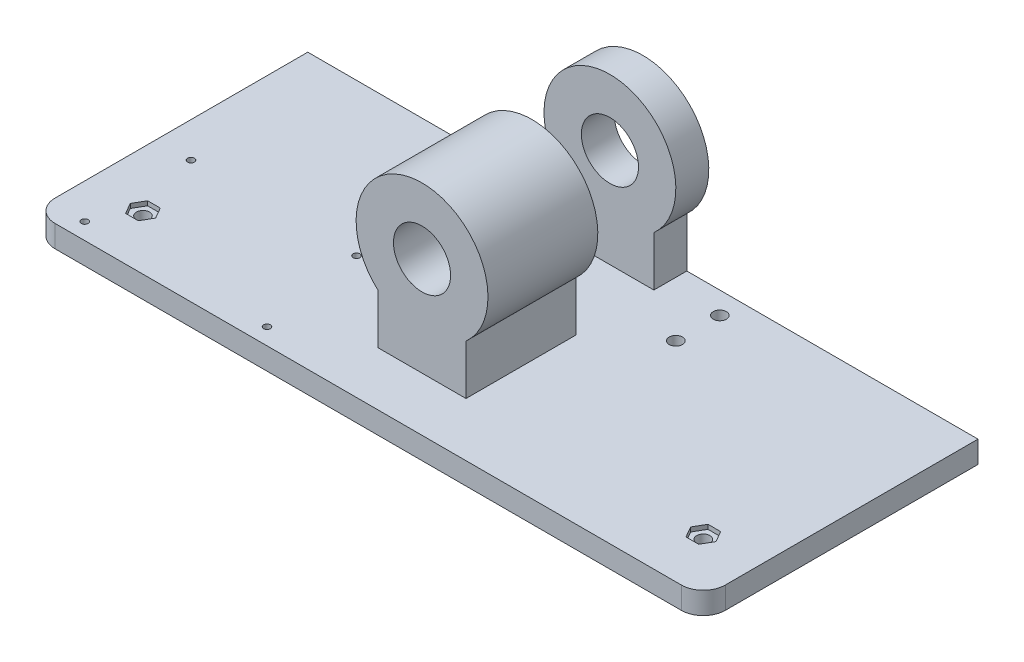
SolidWorks part; units mm, degrees
ref_plane "Front Plane" through (0, 0, 0) normal (0, 0, 1) x (1, 0, 0)
ref_plane "Top Plane" through (0, 0, 0) normal (0, 1, 0) x (1, 0, 0)
ref_plane "Right Plane" through (0, 0, 0) normal (1, 0, 0) x (0, 0, -1)
sketch "Sketch1" plane through (0, 0, 0) normal (0, 1, 0) x (1, 0, 0)
  line L0 (152.5, 125) -> (152.5, 0) construction
  line L1 (0, 0) -> (305, 0)
  line L2 (0, 0) -> (0, 125)
  line L3 (0, 125) -> (305, 125)
  line L4 (305, 0) -> (305, 125)
  line L5 (25, 100) -> (280, 100) construction
  line L6 (280, 25) -> (280, 100) construction
  line L7 (25, 25) -> (280, 25) construction
  line L8 (25, 25) -> (25, 100) construction
  line L9 (152.5, 62.5) -> (25, 62.5) construction
  line L10 (30.7735, 100) -> (27.8868, 105) construction
  line L11 (27.8868, 105) -> (22.1132, 105) construction
  line L12 (22.1132, 105) -> (19.2265, 100) construction
  line L13 (19.2265, 100) -> (22.1132, 95) construction
  line L14 (22.1132, 95) -> (27.8868, 95) construction
  line L15 (27.8868, 95) -> (30.7735, 100) construction
  line L16 (27.8868, 30) -> (30.7735, 25) construction
  line L17 (22.1132, 30) -> (27.8868, 30) construction
  line L18 (19.2265, 25) -> (22.1132, 30) construction
  line L19 (22.1132, 20) -> (19.2265, 25) construction
  line L20 (27.8868, 20) -> (22.1132, 20) construction
  line L21 (30.7735, 25) -> (27.8868, 20) construction
  line L22 (282.8868, 30) -> (277.1132, 30) construction
  line L23 (285.7735, 25) -> (282.8868, 30) construction
  line L24 (282.8868, 20) -> (285.7735, 25) construction
  line L25 (277.1132, 20) -> (282.8868, 20) construction
  line L26 (274.2265, 25) -> (277.1132, 20) construction
  line L27 (277.1132, 30) -> (274.2265, 25) construction
  line L28 (277.1132, 95) -> (274.2265, 100) construction
  line L29 (282.8868, 95) -> (277.1132, 95) construction
  line L30 (285.7735, 100) -> (282.8868, 95) construction
  line L31 (282.8868, 105) -> (285.7735, 100) construction
  line L32 (277.1132, 105) -> (282.8868, 105) construction
  line L33 (274.2265, 100) -> (277.1132, 105) construction
  line L34 (107.5, 115) -> (107.5, 125) construction
  line L35 (132.5, 0) -> (172.5, 0) construction
  line L37 (132.5, 125) -> (172.5, 125) construction
  line L41 (132.5, 25) -> (172.5, 25) construction
  line L50 (305, 14.5) -> (253.3, 14.5) construction
  line L51 (30.7735, 100) -> (22.1132, 105) construction
  line L54 (0, 125) -> (90.0836, 125) construction
  line L55 (0, 125) -> (0, 84.5) construction
  line L62 (0, 84.5) -> (0, 69.5) construction
  line L64 (62, 0) -> (62, 125) construction
  line L65 (253.3, 14.5) -> (253.3, 0) construction
  line L67 (253.3, 14.5) -> (280.2, 14.5) construction
  circle A1 centre (25, 100) radius 5 construction
  circle A3 centre (280, 25) radius 3
  circle A4 centre (25, 25) radius 3
  circle A18 centre (107.5, 115) radius 3
  circle A20 centre (107.5, 95) radius 3
  circle A23 centre (197.5, 115) radius 3
  circle A24 centre (197.5, 95) radius 3
  circle A27 centre (107.5, 75) radius 3 [skipped]
  circle A28 centre (107.5, 55) radius 3 [skipped]
  point P49 (122.5, 113.2246)
  dimension "D3" = 6
  dimension "D1" = 305
  dimension "D2" = 125
  dimension "D5" = 10
  dimension "D6" = 40
  dimension "D15" = 62
  dimension "D18" = 51.7
  dimension "D19" = 14.5
  dimension "D20" = 26.9
  dimension "D8" = 20
  dimension "D9" = 45
  dimension "D4" = 25
  dimension "D14" = 2
  dimension "D7" = 4
extrude "Boss-Extrude1" add sketch "Sketch1" along normal blind 10
sketch "Sketch7" plane through (0, 10, 0) normal (0, 1, 0) x (1, 0, 0)
  line L0 (0, 0) -> (305, 0) construction
  line L1 (132.5, 24.5) -> (172.5, 24.5)
  line L2 (132.5, 24.5) -> (132.5, 74.5)
  line L3 (132.5, 74.5) -> (172.5, 74.5)
  line L4 (172.5, 24.5) -> (172.5, 74.5)
  line L5 (152.5, 0) -> (152.5, 125) construction
  line L6 (305, 125) -> (0, 125) construction
  line L18 (132.5, 110) -> (172.5, 110)
  line L19 (132.5, 110) -> (132.5, 125)
  line L20 (132.5, 125) -> (172.5, 125)
  line L21 (172.5, 110) -> (172.5, 125)
  point P11 (152.5, 74.5)
  point P20 (152.5, 110)
  dimension "D1" = 40
  dimension "D2" = 50
  dimension "D4" = 15
  dimension "D3" = 35.5
extrude "Boss-Extrude2" add sketch "Sketch7" along normal blind 22.6393
sketch "Sketch11" plane through (0, 0, -24.5) normal (0, 0, 1) x (1, 0, 0)
  circle A0 centre (152.5, 55) radius 30
  circle A1 centre (152.5, 55) radius 13
  dimension "D1" = 60
  dimension "D2" = 26
extrude "Boss-Extrude3" add sketch "Sketch11" against normal up to surface (100.5 mm away) up to face at (152.5, 13.1598, -125)
ref_plane "Plane1" through (0, 0, -62.5) normal (0, 0, 1) x (1, 0, 0)
sketch "Sketch12" plane through (305, 0, 0) normal (1, 0, 0) x (0, 0, -1)
  line L0 (125, 85) -> (24.5, 85) construction
  line L1 (74.5, 10) -> (110, 10)
  line L2 (74.5, 10) -> (74.5, 85)
  line L3 (74.5, 85) -> (110, 85)
  line L4 (110, 10) -> (110, 85)
  line L6 (110, 32.6393) -> (110, 10) construction
extrude "Cut-Extrude2" cut sketch "Sketch12" against normal through all
sketch "Sketch6" plane through (0, 10, 0) normal (0, 1, 0) x (1, 0, 0)
  line L0 (152.5, 125) -> (152.5, 0) construction
  line L8 (0, 0) -> (305, 0) construction
  line L9 (152.5, 62.5) -> (0, 62.5) construction
  line L10 (0, 125) -> (0, 0) construction
  line L29 (27.8868, 30) -> (30.7735, 25)
  line L30 (274.2265, 25) -> (277.1132, 20)
  line L31 (277.1132, 20) -> (282.8868, 20)
  line L32 (282.8868, 20) -> (285.7735, 25)
  line L33 (285.7735, 25) -> (282.8868, 30)
  line L34 (282.8868, 30) -> (277.1132, 30)
  line L35 (277.1132, 30) -> (274.2265, 25)
  line L36 (22.1132, 30) -> (27.8868, 30)
  line L37 (19.2265, 25) -> (22.1132, 30)
  line L38 (22.1132, 20) -> (19.2265, 25)
  line L39 (27.8868, 20) -> (22.1132, 20)
  line L40 (30.7735, 25) -> (27.8868, 20)
  circle A0 centre (280, 25) radius 5 construction
  dimension "D1" = 10
extrude "Cut-Extrude1" cut sketch "Sketch6" against normal blind 2
sketch "Sketch16" plane through (0, 10, 0) normal (0, 1, 0) x (1, 0, 0)
  line L0 (0, 0) -> (305, 0) construction
  line L1 (0, 125) -> (0, 0) construction
  circle A0 centre (16, 7.5) radius 1.55
  circle A1 centre (98.95, 7.5) radius 1.55
  circle A2 centre (16, 55.866) radius 1.55
  circle A3 centre (91.33, 55.866) radius 1.55
  dimension "D1" = 3.1
  dimension "D2" = 7.5
  dimension "D3" = 82.95
  dimension "D4" = 16
  dimension "D5" = 48.366
  dimension "D6" = 75.33
extrude "Cut-Extrude3" cut sketch "Sketch16" against normal through all
fillet "Fillet3" radius 10 2 edges at (305, 5, 0) (0, 5, 0)
chamfer "Chamfer2" distance 1.65 4 edges at (98.95, 0, -5.95) (91.33, 0, -54.316) (16, 0, -5.95) (16, 0, -54.316)
equation "\"joint_width\"=4"
equation "\"short_base_length\"=12.5"
equation "\"D2@Sketch1\"=\"short_base_length\""
equation "\"outer_diam_main_joint\"=6"
equation "\"D1@Sketch11\"=\"outer_diam_main_joint\""
equation "\"D1@Sketch7\"=\"outer_diam_main_joint\"-2"
equation "\"D1@Boss-Extrude2\"=(\"outer_diam_main_joint\"/2)+1.5cm-sqr((\"outer_diam_main_joint\"/2)^2-((\"outer_diam_main_joint\"-2)/2)^2)"
equation "\"D6@Sketch1\"=\"outer_diam_main_joint\"-2"
equation "\"pulleyside\"=1.5"
